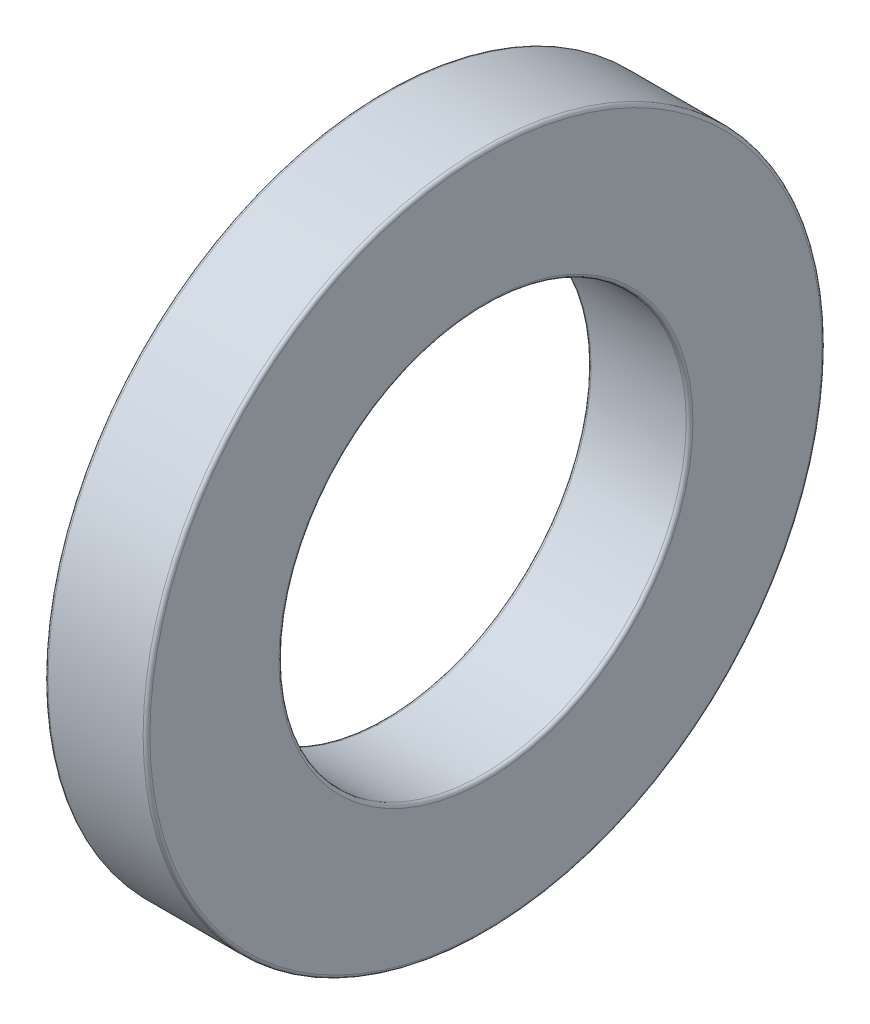
SolidWorks part; units mm, degrees
ref_plane "Front Plane" through (0, 0, 0) normal (0, 0, 1) x (1, 0, 0)
ref_plane "Top Plane" through (0, 0, 0) normal (0, 1, 0) x (1, 0, 0)
ref_plane "Right Plane" through (0, 0, 0) normal (1, 0, 0) x (0, 0, -1)
sketch "Sketch1" plane through (0, 0, 0) normal (1, 0, 0) x (0, 0, -1)
  circle A0 centre (0, 0) radius 5
  circle A1 centre (0, 0) radius 3
  dimension "D1" = 6
  dimension "D2" = 10
extrude "Boss-Extrude1" add sketch "Sketch1" along normal blind 1.5
fillet "Fillet1" radius 0.05 4 edges at (0, 0, -5) (0, 0, -3) (1.5, 0, -3) (1.5, 0, -5)
